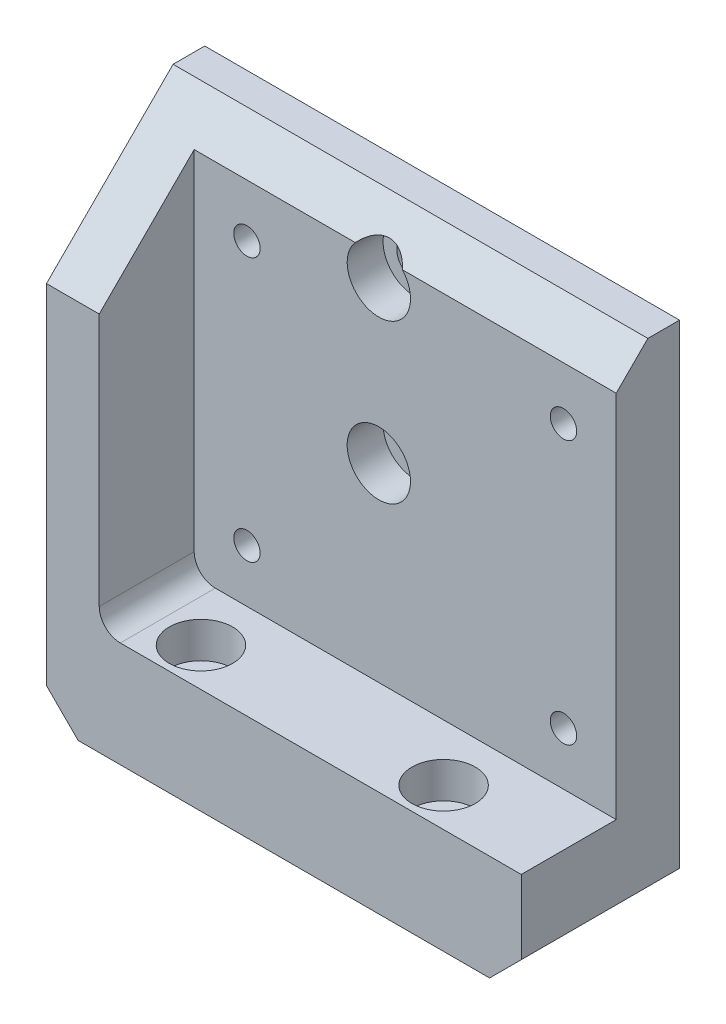
SolidWorks part; units mm, degrees
material "6061 Alloy"
ref_plane "Front Plane" through (0, 0, 0) normal (0, 0, 1) x (1, 0, 0)
ref_plane "Top Plane" through (0, 0, 0) normal (0, 1, 0) x (1, 0, 0)
ref_plane "Right Plane" through (0, 0, 0) normal (1, 0, 0) x (0, 0, -1)
sketch "Sketch1" plane through (0, 0, 0) normal (0, 0, 1) x (1, 0, 0)
  line L1 (-22.5, 24) -> (22.5, 24)
  line L2 (-22.5, 24) -> (-22.5, -24)
  line L3 (-22.5, -24) -> (22.5, -24)
  line L4 (22.5, 24) -> (22.5, -24)
  line L5 (-22.5, 24) -> (22.5, -24) construction
  line L6 (-22.5, -24) -> (22.5, 24) construction
  dimension "D1" = 45
  dimension "D2" = 48
extrude "Boss-Extrude1" add sketch "Sketch1" along normal blind 6
sketch "Sketch2" plane through (0, -24, 0) normal (0, -1, 0) x (1, 0, 0)
  line L0 (-22.5, 0) -> (22.5, 0) construction
  line L1 (22.5, 0) -> (-22.5, 0)
  line L2 (22.5, 0) -> (22.5, 15)
  line L3 (22.5, 15) -> (-22.5, 15)
  line L4 (-22.5, 0) -> (-22.5, 15)
  line L5 (22.5, 6) -> (22.5, 0) construction
  dimension "D1" = 15
extrude "Boss-Extrude2" add sketch "Sketch2" against normal blind 10
hole_wizard "CBORE for M3 Hexagon socket head cap screws1" positions "Sketch3" profile "Sketch5" counterbore size "M3" standard "GB"
sketch "Sketch3" plane through (0, -14, 0) normal (0, 1, 0) x (1, 0, 0)
  line L0 (0, -3.3) -> (0, 3.3) construction
  point P0 (-11.5, -11.36)
  point P3 (11.5, -11.36)
  dimension "D1" = 23
  dimension "D2" = 11.36
sketch "Sketch5" plane through (-11.5, -14, 11.36) normal (1, 0, 0) x (0, 0, 1)
  line L0 (0, 0) -> (0, 16.0215)
  line L1 (0, 16.0215) -> (1.7, 15)
  line L2 (1.7, 15) -> (1.7, 3.4)
  line L3 (1.7, 3.4) -> (3, 3.4)
  line L4 (3, 3.4) -> (3, 0)
  line L5 (3, 0) -> (0, 0)
  line L10 (0, 16.0215) -> (-1.7, 15) construction
  line L11 (0, -6.35) -> (0, 107.95) construction
  dimension "Hole Dia." = 3.4
  dimension "Hole Depth" = 15
  dimension "C'Bore Dia." = 6
  dimension "C'Bore Depth" = 3.4
  dimension "Drill Angle" = 118
sketch "Sketch6" plane through (0, 0, 6) normal (0, 0, 1) x (1, 0, 0)
  line L0 (-22.5, -14) -> (22.5, -14) construction
  line L1 (-22.5, 24) -> (-17.5, 24)
  line L2 (-22.5, 24) -> (-22.5, -14)
  line L3 (-22.5, -14) -> (-17.5, -14)
  line L4 (-17.5, 24) -> (-17.5, -14)
  dimension "D1" = 5
extrude "Boss-Extrude3" add sketch "Sketch6" along normal up to surface (9 mm away) up to face at (0, -19, 15)
fillet "Fillet1" radius 2 1 edges at (-17.5, -14, 10.5)
hole_wizard "CBORE for M3 Hexagon socket head cap screws2" positions "Sketch7" profile "Sketch8" counterbore size "M3" standard "GB" end condition through all
sketch "Sketch7" plane through (0, 0, 6) normal (0, 0, 1) x (1, 0, 0)
  line L0 (22.5, 24) -> (-17.5, 24) construction
  point P0 (0, 19)
  point P2 (0, 4)
  dimension "D1" = 5
  dimension "D2" = 15
sketch "Sketch8" plane through (0, 19, 6) normal (1, 0, 0) x (0, -1, 0)
  line L0 (0, 0) -> (0, 6)
  line L1 (0, 6) -> (1.7, 6)
  line L3 (1.7, 6) -> (1.7, 3.4)
  line L4 (1.7, 3.4) -> (3, 3.4)
  line L5 (3, 3.4) -> (3, 0)
  line L7 (3, 0) -> (0, 0)
  line L11 (0, -6.35) -> (0, 107.95) construction
  dimension "Thru Hole Dia." = 3.4
  dimension "Thru Hole Depth" = 6
  dimension "C'Bore Dia." = 6
  dimension "C'Bore Depth" = 3.4
chamfer "Chamfer3" distance 3 angle 45 2 edges at (22.5, -24, 7.5) (-22.5, -24, 7.5)
sketch "Sketch9" plane through (22.5, 0, 0) normal (1, 0, 0) x (0, 0, -1)
  line L1 (-6, 24) -> (0, 24) construction
  line L2 (-3, 24) -> (-15, 12)
  line L3 (-15, -12) -> (-15, 24) construction
  line L4 (-15, 24) -> (-6, 24) construction
  dimension "D1" = 45
  dimension "D2" = 12
extrude "Cut-Extrude1" cut sketch "Sketch9" against normal through all and the other way through all flip side to cut
hole_wizard "M3 Tapped Hole1" positions "Sketch10" profile "Sketch11" tap size "M3" standard "GB"
sketch "Sketch10" plane through (0, 0, 6) normal (0, 0, 1) x (1, 0, 0)
  line L0 (-17.5, 21) -> (-17.5, 12) construction
  line L1 (-17.5, 21) -> (-2.2361, 21) construction
  line L2 (22.5, -14) -> (22.5, 21) construction
  line L3 (-15.5, -14) -> (22.5, -14) construction
  point P0 (-12.5, 16)
  point P2 (17.5, 16)
  point P4 (-12.5, -9)
  point P6 (17.5, -9)
  dimension "D1" = 5
  dimension "D2" = 5
  dimension "D3" = 5
  dimension "D4" = 5
sketch "Sketch11" plane through (-12.5, 16, 6) normal (1, 0, 0) x (0, -1, 0)
  line L0 (0, 0) -> (0, 4.7511)
  line L1 (0, 4.7511) -> (1.25, 4)
  line L2 (1.25, 4) -> (1.25, 0)
  line L5 (1.25, 0) -> (0, 0)
  line L10 (0, 4.7511) -> (-1.25, 4) construction
  line L11 (0, -6.35) -> (0, 107.95) construction
  dimension "Tap Drill Dia." = 2.5
  dimension "Tap Drill Depth" = 4
  dimension "Drill Angle" = 118
cosmetic thread "Hole Thread1" parameters "D1"=6, "D2"=3
cosmetic thread "Hole Thread2" parameters "D1"=6, "D2"=3
cosmetic thread "Hole Thread3" parameters "D1"=6, "D2"=3
cosmetic thread "Hole Thread4" parameters "D1"=6, "D2"=3
